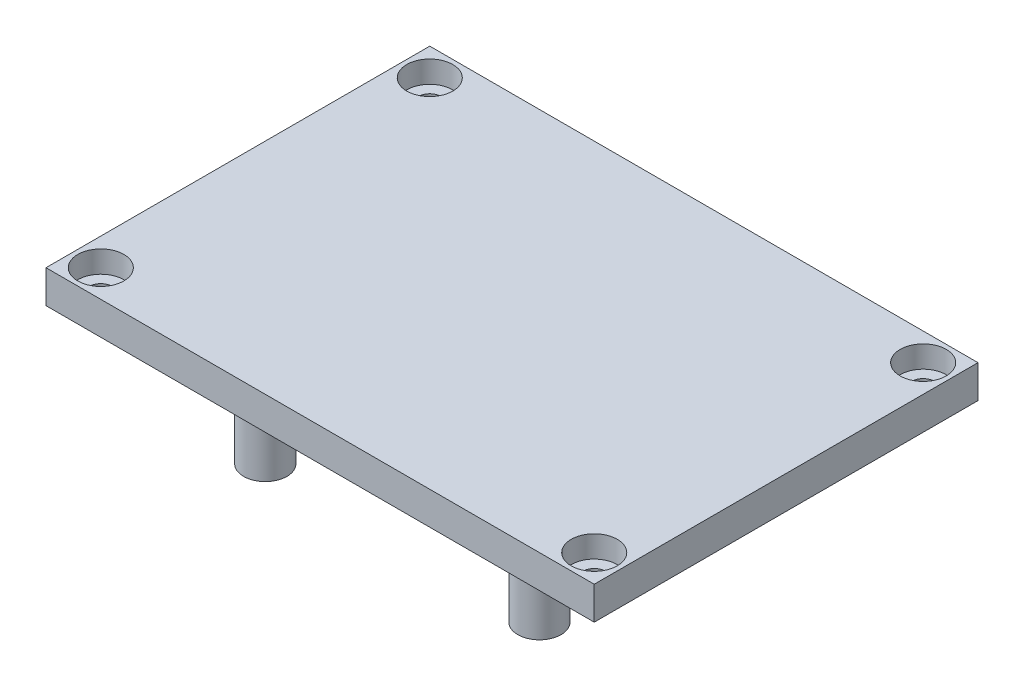
SolidWorks part; units mm, degrees
ref_plane "Ebene vorne" through (0, 0, 0) normal (0, 0, 1) x (1, 0, 0)
ref_plane "Ebene oben" through (0, 0, 0) normal (0, 1, 0) x (1, 0, 0)
ref_plane "Ebene rechts" through (0, 0, 0) normal (1, 0, 0) x (0, 0, -1)
sketch "Skizze1" plane through (0, 0, 0) normal (0, 1, 0) x (1, 0, 0)
  line L4 (-50, -35) -> (50, -35)
  line L5 (50, -35) -> (50, 35)
  line L6 (50, 35) -> (-15.0246, 35)
  line L7 (-50, 35) -> (-50, -35)
  line L8 (-50, -35) -> (50, -35)
  line L9 (50, -35) -> (50, 35)
  line L10 (50, 35) -> (-15.0246, 35)
  line L11 (-50, 35) -> (-50, -35)
  line L72 (-15.0246, 33) -> (-35.0246, 33) construction
  line L73 (-15.0246, 35) -> (-35.0246, 35)
  line L92 (-15.0246, 35) -> (-15.0246, 33)
  line L93 (-15.0246, 35) -> (-15.0246, 33) construction
  line L94 (-15.0246, 33) -> (39.9, 33)
  line L95 (-15.0246, 33) -> (39.9, 33) construction
  line L96 (39.9, 33) -> (39.9, 30)
  line L97 (39.9, 33) -> (39.9, 30) construction
  line L98 (45, 24.9) -> (48, 24.9)
  line L99 (45, 24.9) -> (48, 24.9) construction
  line L100 (48, 24.9) -> (48, -24.9)
  line L101 (48, 24.9) -> (48, -24.9) construction
  line L102 (48, -24.9) -> (45, -24.9)
  line L103 (48, -24.9) -> (45, -24.9) construction
  line L104 (39.9, -30) -> (39.9, -33)
  line L105 (39.9, -30) -> (39.9, -33) construction
  line L106 (39.9, -33) -> (-39.9, -33)
  line L107 (39.9, -33) -> (-39.9, -33) construction
  line L108 (-39.9, -33) -> (-39.9, -30)
  line L109 (-39.9, -33) -> (-39.9, -30) construction
  line L110 (-45, -24.9) -> (-48, -24.9)
  line L111 (-45, -24.9) -> (-48, -24.9) construction
  line L112 (-48, -24.9) -> (-48, 24.9)
  line L113 (-48, -24.9) -> (-48, 24.9) construction
  line L114 (-48, 24.9) -> (-45, 24.9)
  line L115 (-48, 24.9) -> (-45, 24.9) construction
  line L116 (-39.9, 30) -> (-39.9, 33)
  line L117 (-39.9, 30) -> (-39.9, 33) construction
  line L118 (-39.9, 33) -> (-35.0246, 33)
  line L119 (-39.9, 33) -> (-35.0246, 33) construction
  line L120 (-35.0246, 33) -> (-35.0246, 35)
  line L121 (-35.0246, 33) -> (-35.0246, 35) construction
  line L122 (-35.0246, 35) -> (-50, 35)
  line L123 (-35.0246, 35) -> (-50, 35)
  arc A8 (39.9, 30) -> (45, 24.9) centre (45, 30) ccw
  arc A9 (39.9, 30) -> (45, 24.9) centre (45, 30) ccw construction
  arc A10 (45, -24.9) -> (39.9, -30) centre (45, -30) ccw
  arc A11 (45, -24.9) -> (39.9, -30) centre (45, -30) ccw construction
  arc A12 (-39.9, -30) -> (-45, -24.9) centre (-45, -30) ccw
  arc A13 (-39.9, -30) -> (-45, -24.9) centre (-45, -30) ccw construction
  arc A14 (-45, 24.9) -> (-39.9, 30) centre (-45, 30) ccw
  arc A15 (-45, 24.9) -> (-39.9, 30) centre (-45, 30) ccw construction
  dimension "D1" = 0
extrude "Aufsatz-Linear austragen1" add sketch "Skizze1" along normal blind 6
sketch "Skizze2" plane through (0, 0, 0) normal (0, -1, 0) x (-1, 0, 0)
  line L0 (39.9, -33) -> (-39.9, -33) construction
  line L1 (-39.9, -33) -> (-39.9, -30) construction
  line L2 (-45, -24.9) -> (-48, -24.9) construction
  line L3 (-48, -24.9) -> (-48, 24.9) construction
  line L4 (-48, 24.9) -> (-45, 24.9) construction
  line L5 (-39.9, 30) -> (-39.9, 33) construction
  line L7 (39.9, 33) -> (39.9, 30) construction
  line L8 (45, 24.9) -> (48, 24.9) construction
  line L9 (48, 24.9) -> (48, -24.9) construction
  line L10 (48, -24.9) -> (45, -24.9) construction
  line L11 (39.9, -33) -> (-39.9, -33) construction
  line L12 (-39.9, -33) -> (-39.9, -30) construction
  line L13 (-45, -24.9) -> (-48, -24.9) construction
  line L14 (-48, -24.9) -> (-48, 24.9) construction
  line L15 (-48, 24.9) -> (-45, 24.9) construction
  line L16 (-39.9, 30) -> (-39.9, 33) construction
  line L17 (-39.9, 33) -> (39.9, 33) construction
  line L18 (39.9, 33) -> (39.9, 30) construction
  line L19 (45, 24.9) -> (48, 24.9) construction
  line L20 (48, 24.9) -> (48, -24.9) construction
  line L21 (48, -24.9) -> (45, -24.9) construction
  line L22 (39.9, -30) -> (39.9, -33) construction
  line L23 (39.9, -30) -> (39.9, -33) construction
  line L24 (39.65, -32.75) -> (-39.65, -32.75)
  line L25 (-39.65, -32.75) -> (-39.65, -30)
  line L26 (-45, -24.65) -> (-47.75, -24.65)
  line L27 (-47.75, -24.65) -> (-47.75, 24.65)
  line L28 (-47.75, 24.65) -> (-45, 24.65)
  line L29 (-39.65, 30) -> (-39.65, 32.75)
  line L30 (-39.65, 32.75) -> (39.65, 32.75)
  line L31 (39.65, 32.75) -> (39.65, 30)
  line L32 (45, 24.65) -> (47.75, 24.65)
  line L33 (47.75, 24.65) -> (47.75, -24.65)
  line L34 (47.75, -24.65) -> (45, -24.65)
  line L35 (39.65, -30) -> (39.65, -32.75)
  line L36 (45.75, 22.65) -> (45.75, -22.65)
  line L37 (45.75, -22.65) -> (45, -22.65)
  line L38 (37.65, -30) -> (37.65, -30.75)
  line L39 (37.65, -30.75) -> (-37.65, -30.75)
  line L40 (-37.65, -30.75) -> (-37.65, -30)
  line L41 (-45, -22.65) -> (-45.75, -22.65)
  line L42 (-45.75, -22.65) -> (-45.75, 22.65)
  line L43 (-45.75, 22.65) -> (-45, 22.65)
  line L44 (-37.65, 30) -> (-37.65, 30.75)
  line L45 (-37.65, 30.75) -> (37.65, 30.75)
  line L46 (37.65, 30.75) -> (37.65, 30)
  line L47 (45, 22.65) -> (45.75, 22.65)
  arc A0 (45, -24.9) -> (39.9, -30) centre (45, -30) ccw construction
  arc A1 (45, -24.9) -> (39.9, -30) centre (45, -30) ccw construction
  arc A2 (-39.9, -30) -> (-45, -24.9) centre (-45, -30) ccw construction
  arc A3 (-45, 24.9) -> (-39.9, 30) centre (-45, 30) ccw construction
  arc A4 (39.9, 30) -> (45, 24.9) centre (45, 30) ccw construction
  arc A5 (-39.9, -30) -> (-45, -24.9) centre (-45, -30) ccw construction
  arc A6 (-45, 24.9) -> (-39.9, 30) centre (-45, 30) ccw construction
  arc A7 (39.9, 30) -> (45, 24.9) centre (45, 30) ccw construction
  arc A8 (-39.65, -30) -> (-45, -24.65) centre (-45, -30) ccw
  arc A9 (-45, 24.65) -> (-39.65, 30) centre (-45, 30) ccw
  arc A10 (39.65, 30) -> (45, 24.65) centre (45, 30) ccw
  arc A11 (45, -24.65) -> (39.65, -30) centre (45, -30) ccw
  arc A12 (45, -22.65) -> (37.65, -30) centre (45, -30) ccw
  arc A13 (-37.65, -30) -> (-45, -22.65) centre (-45, -30) ccw
  arc A14 (-45, 22.65) -> (-37.65, 30) centre (-45, 30) ccw
  arc A15 (37.65, 30) -> (45, 22.65) centre (45, 30) ccw
  dimension "D1" = 0.25
  dimension "D2" = 2
extrude "Aufsatz-Linear austragen2" add sketch "Skizze2" along normal blind 2
sketch "Skizze3" plane through (0, 6, 0) normal (0, 1, 0) x (1, 0, 0)
  line L4 (-50, 35) -> (-50, -35)
  line L5 (-50, -35) -> (50, -35)
  line L6 (50, -35) -> (50, 35)
  line L7 (50, 35) -> (-50, 35)
  line L8 (-50, 35) -> (-50, -35)
  line L9 (-50, -35) -> (50, -35)
  line L10 (50, -35) -> (50, 35)
  line L11 (50, 35) -> (-50, 35)
  circle A0 centre (-45, -30) radius 2.1 construction
  circle A1 centre (-45, 30) radius 2.1 construction
  circle A2 centre (45, -30) radius 2.1 construction
  circle A3 centre (45, 30) radius 2.1 construction
  circle A4 centre (-45, -30) radius 2.1
  circle A5 centre (-45, 30) radius 2.1
  circle A6 centre (45, -30) radius 2.1
  circle A7 centre (45, 30) radius 2.1
  dimension "D1" = 0
extrude "Schnitt-Linear austragen1" cut sketch "Skizze3" against normal up to next (6 mm away) flip side to cut
sketch "Skizze4" plane through (0, 6, 0) normal (0, 1, 0) x (1, 0, 0)
  circle A0 centre (-45, 30) radius 2.1 construction
  circle A1 centre (-45, -30) radius 2.1 construction
  circle A4 centre (45, 30) radius 2.1 construction
  circle A6 centre (45, -30) radius 2.1 construction
  circle A7 centre (-45, -30) radius 2.1 construction
  circle A8 centre (45, -30) radius 2.1 construction
  circle A9 centre (45, 30) radius 2.1 construction
  circle A10 centre (-45, 30) radius 2.1 construction
  circle A11 centre (-45, -30) radius 4.2
  circle A12 centre (45, -30) radius 4.2
  circle A13 centre (45, 30) radius 4.2
  circle A14 centre (-45, 30) radius 4.2
  dimension "D1" = 2.1
extrude "Schnitt-Linear austragen2" cut sketch "Skizze4" against normal blind 4
sketch "Skizze5" plane through (0, 0, 0) normal (0, -1, 0) x (-1, 0, 0)
  line L0 (0, 41.5441) -> (0, -42.3421) construction
  line L1 (-66.5797, 0) -> (95.8513, 0) construction
  circle A0 centre (25, -20) radius 3.95
  circle A1 centre (25, -20) radius 1.45
  circle A2 centre (-25, -20) radius 1.45
  circle A3 centre (-25, -20) radius 3.95
  circle A4 centre (-25, 20) radius 3.95
  circle A5 centre (-25, 20) radius 1.45
  circle A6 centre (25, 20) radius 1.45
  circle A7 centre (25, 20) radius 3.95
  dimension "D1" = 2.9
  dimension "D2" = 2.5
  dimension "D4" = 50
  dimension "D6" = 40
extrude "Aufsatz-Linear austragen3" add sketch "Skizze5" along normal blind 20
